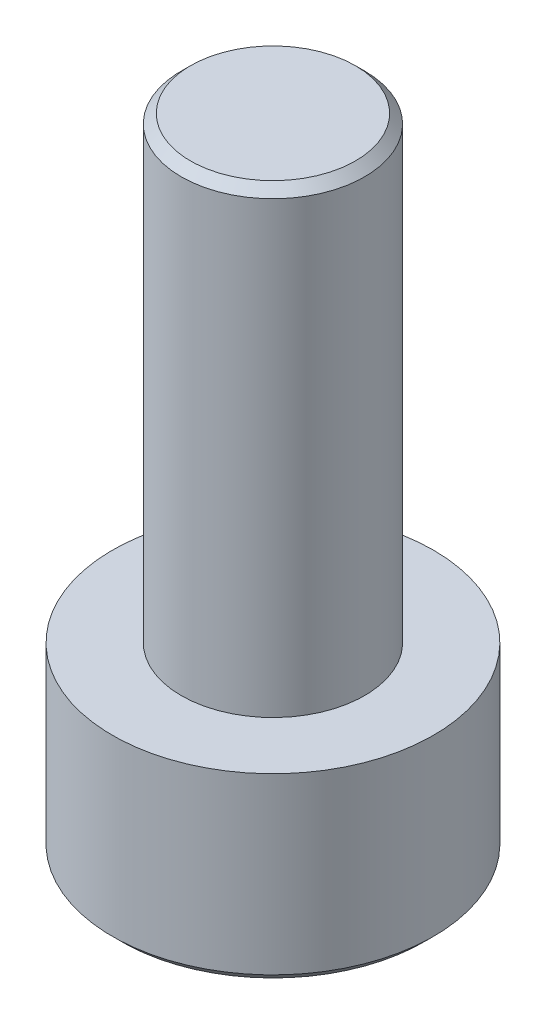
SolidWorks part; units mm, degrees
ref_plane "Front Plane" through (0, 0, 0) normal (0, 0, 1) x (1, 0, 0)
ref_plane "Top Plane" through (0, 0, 0) normal (0, 1, 0) x (1, 0, 0)
ref_plane "Right Plane" through (0, 0, 0) normal (1, 0, 0) x (0, 0, -1)
sketch "Reconstructed nominal axial profile" plane through (0, 0, 0) normal (0, 0, 1) x (1, 0, 0)
  line L0 (0, -500) -> (0, 50) construction
  line L1 (0, -4) -> (3.3, -4)
  line L2 (3.3, -4) -> (3.5, -3.8)
  line L3 (3.5, -3.8) -> (3.5, 0)
  line L4 (3.5, 0) -> (2, 0)
  line L5 (2, 0) -> (2, 9.8)
  line L6 (2, 9.8) -> (1.8, 10)
  line L7 (1.8, 10) -> (0, 10)
  line L8 (0, 10) -> (0, -4)
revolve "Native revolved geometry" add sketch "Reconstructed nominal axial profile" angle 360 about L0
sketch "Sketch2" plane through (0, 0, 0) normal (0, 1, 0) x (1, 0, 0)
  line L0 (1.7321, 0) -> (0.866, -1.5)
  line L1 (0.866, -1.5) -> (-0.866, -1.5)
  line L2 (-0.866, -1.5) -> (-1.7321, 0)
  line L3 (-1.7321, 0) -> (-0.866, 1.5)
  line L4 (-0.866, 1.5) -> (0.866, 1.5)
  line L5 (0.866, 1.5) -> (1.7321, 0)
extrude "Simplified nominal hex socket" cut sketch "Sketch2" along normal blind 2 from offset 4
